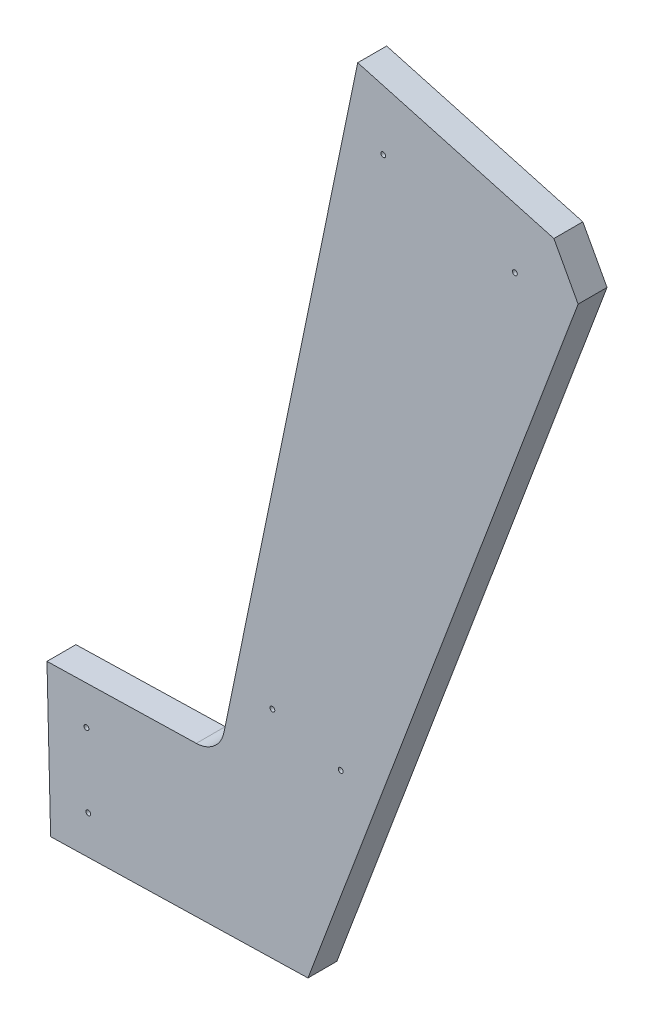
SolidWorks part; units mm, degrees
material "Beech"
ref_plane "Front Plane" through (0, 0, 0) normal (0, 0, 1) x (1, 0, 0)
ref_plane "Top Plane" through (0, 0, 0) normal (0, 1, 0) x (1, 0, 0)
ref_plane "Right Plane" through (0, 0, 0) normal (1, 0, 0) x (0, 0, -1)
sketch "Sketch1" plane through (0, 0, 0) normal (0, 0, 1) x (1, 0, 0)
  line L0 (-61.7531, -505.1337) -> (-59.3403, -603.9479)
  line L1 (-70.6552, -530.7587) -> (-61.1331, -530.5262) construction
  line L12 (272.1416, -96.993) -> (142.9339, -61.3062)
  line L13 (142.9339, -61.3062) -> (54.7807, -487.5464)
  line L14 (36.5905, -502.7325) -> (-61.7531, -505.1337)
  line L16 (-59.3403, -603.9479) -> (110.1577, -599.8093)
  line L17 (110.1577, -599.8093) -> (288.0944, -126.4487)
  line L37 (288.0944, -126.4487) -> (272.1416, -96.993)
  arc A0 (54.7807, -487.5464) -> (36.5905, -502.7325) centre (36.1255, -483.6882) cw
  point P2 (158.986, -65.7398)
  point P8 (0, 0)
  point P9 (27.8432, -502.9461)
  point P10 (0, 0)
  point P11 (44.9881, -505.1337)
  point P13 (45.0704, -478.1829)
  point P14 (40.5215, -493.3922)
  point P15 (-61.1331, -505.1186)
  point P16 (0, 0)
  point P17 (158.986, -65.7398)
  point P18 (0, 0)
  point P19 (0, 0)
  point P20 (288.0944, -126.4487)
  point P21 (0, 0)
  point P22 (272.1416, -96.993)
  point P23 (142.9339, -61.3062)
  point P24 (60.0376, -462.1282)
  point P25 (57.7438, -473.2189)
  point P26 (27.8432, -505.1337)
  point P27 (0, 0)
  point P28 (95.5097, -501.2939)
  point P29 (45.8781, -530.5262)
  point P31 (0, 0)
  dimension "D2" = 19.05
  dimension "D1" = 112
  dimension "D3" = 9.525
  dimension "D4" = 98.8437
extrude "Boss-Extrude1" add sketch "Sketch1" along normal blind 19.05
hole_wizard "Hole1" [suppressed] positions "Sketch2" profile "Sketch3" legacy
sketch "Sketch2" plane through (162.2459, -21.7021, -146.425) normal (-0.9639, 0.2662, 0) x (0, 0, -1)
  line L8 (155.95, -2.2757) -> (155.95, 437.7664) construction
  line L11 (175, -2.2757) -> (175, 437.7664) construction
  line L15 (155.95, -2.2757) -> (155.95, 107.7348)
  line L16 (155.95, 107.7348) -> (155.95, 217.7454)
  line L17 (155.95, 217.7454) -> (155.95, 327.7559)
  line L18 (155.95, 327.7559) -> (155.95, 437.7664)
  line L20 (175, -2.2757) -> (175, 85.7327)
  line L21 (175, 85.7327) -> (175, 173.7411)
  line L22 (175, 173.7411) -> (175, 261.7496)
  line L23 (175, 261.7496) -> (175, 349.758)
  line L24 (175, 349.758) -> (175, 437.7664)
  line L25 (0, 155.0243) -> (0, 437.7664) construction
  point P36 (155.95, 107.7348)
  point P40 (155.95, 327.7559)
  point P46 (175, 85.7327)
  point P52 (175, 349.758)
  point P77 (-175, 349.758)
  point P80 (-175, 85.7327)
  point P81 (-155.95, 327.7559)
  point P83 (-155.95, 107.7348)
sketch "Sketch3" plane through (133.5638, -125.5487, 9.525) normal (0, 0, 1) x (-0.2662, -0.9639, 0)
  line L0 (0, 0) -> (0, 32.7039)
  line L1 (0, 32.7039) -> (1.5875, 31.75)
  line L2 (1.5875, 31.75) -> (1.5875, 4.0177)
  line L3 (1.5875, 4.0177) -> (5.08, 0)
  line L4 (5.08, 0) -> (0, 0)
  line L5 (0, -14.3089) -> (0, 102.4216) construction
  line L6 (0, 32.7039) -> (-1.5875, 31.75) construction
  line L7 (-1.5875, 4.0177) -> (-5.08, 0) construction
  dimension "Diameter" = 3.175
  dimension "Depth" = 31.75
  dimension "C-Sink Diameter" = 10.16
  dimension "C-Sink Angle" = 82
  dimension "Drill Angle" = 118
hole_wizard "Hole2" [suppressed] positions "Sketch4" profile "Sketch5" legacy
sketch "Sketch4" [suppressed] plane through (162.2459, -21.7021, 165.475) normal (-0.9639, 0.2662, 0) x (0, 0, -1)
  line L8 (155.95, -2.2757) -> (155.95, 437.7664) construction
  line L11 (175, -2.2757) -> (175, 437.7664) construction
  line L15 (155.95, -2.2757) -> (155.95, 107.7348)
  line L16 (155.95, 107.7348) -> (155.95, 217.7454)
  line L17 (155.95, 217.7454) -> (155.95, 327.7559)
  line L18 (155.95, 327.7559) -> (155.95, 437.7664)
  line L20 (175, -2.2757) -> (175, 85.7327)
  line L21 (175, 85.7327) -> (175, 173.7411)
  line L22 (175, 173.7411) -> (175, 261.7496)
  line L23 (175, 261.7496) -> (175, 349.758)
  line L24 (175, 349.758) -> (175, 437.7664)
  line L25 (0, 155.0243) -> (0, 437.7664) construction
  point P36 (155.95, 107.7348)
  point P40 (155.95, 327.7559)
  point P46 (175, 85.7327)
  point P52 (175, 349.758)
  point P77 (-175, 349.758)
  point P80 (-175, 85.7327)
  point P81 (-155.95, 327.7559)
  point P83 (-155.95, 107.7348)
sketch "Sketch5" plane through (133.5638, -125.5487, 321.425) normal (0, 0, 1) x (-0.2662, -0.9639, 0)
  line L0 (0, 0) -> (0, 32.7039)
  line L1 (0, 32.7039) -> (1.5875, 31.75)
  line L2 (1.5875, 31.75) -> (1.5875, 4.0177)
  line L3 (1.5875, 4.0177) -> (5.08, 0)
  line L4 (5.08, 0) -> (0, 0)
  line L5 (0, -14.3089) -> (0, 102.4216) construction
  line L6 (0, 32.7039) -> (-1.5875, 31.75) construction
  line L7 (-1.5875, 4.0177) -> (-5.08, 0) construction
  dimension "Diameter" = 3.175
  dimension "Depth" = 31.75
  dimension "C-Sink Diameter" = 10.16
  dimension "C-Sink Angle" = 82
  dimension "Drill Angle" = 118
hole_wizard "Hole3" positions "Sketch6" profile "Sketch7" legacy
sketch "Sketch6" plane through (295.8209, -105.8941, -19.05) normal (0, 0, -1) x (-0.3519, -0.9361, 0)
  line L0 (49.6983, 152.8937) -> (35.888, 0) construction
  line L5 (405.5739, 97.061) -> (396.8068, 0) construction
  line L7 (490.0108, 170.6797) -> (581.6571, 133.6522) construction
  line L12 (503.094, 203.0616) -> (594.7402, 166.0341) construction
  line L16 (586.8736, 410.4235) -> (678.5199, 373.396) construction
  line L19 (558.1066, 143.1672) -> (571.1898, 175.5491) construction
  line L20 (571.1898, 175.5491) -> (654.9694, 382.911) construction
  line L22 (513.5613, 161.1647) -> (526.6445, 193.5466) construction
  line L23 (526.6445, 193.5466) -> (610.4241, 400.9085) construction
  point P0 (47.4133, 127.5967)
  point P2 (39.3155, 37.9455)
  point P4 (403.2889, 71.764)
  point P51 (399.0917, 25.297)
  point P56 (513.5613, 161.1647)
  point P58 (558.1066, 143.1672)
  point P61 (571.1898, 175.5491)
  point P63 (654.9694, 382.911)
  point P66 (526.6445, 193.5466)
  point P68 (610.4241, 400.9085)
  dimension "D4" = 25.4
  dimension "D5" = 38.1
  dimension "D6" = 25.4
  dimension "D7" = 25.4
  dimension "D8" = 25.4
  dimension "D9" = 25.4
sketch "Sketch7" plane through (159.7008, -105.3789, -19.05) normal (1, 0, 0) x (0, 1, 0)
  line L0 (0, 0) -> (0, 39.0539)
  line L1 (0, 39.0539) -> (1.5875, 38.1)
  line L2 (1.5875, 38.1) -> (1.5875, 4.0177)
  line L3 (1.5875, 4.0177) -> (5.08, 0)
  line L4 (5.08, 0) -> (0, 0)
  line L5 (0, -14.3089) -> (0, 102.4216) construction
  line L6 (0, 39.0539) -> (-1.5875, 38.1) construction
  line L7 (-1.5875, 4.0177) -> (-5.08, 0) construction
  dimension "Diameter" = 3.175
  dimension "Depth" = 38.1
  dimension "C-Sink Diameter" = 10.16
  dimension "C-Sink Angle" = 82
  dimension "Drill Angle" = 118
